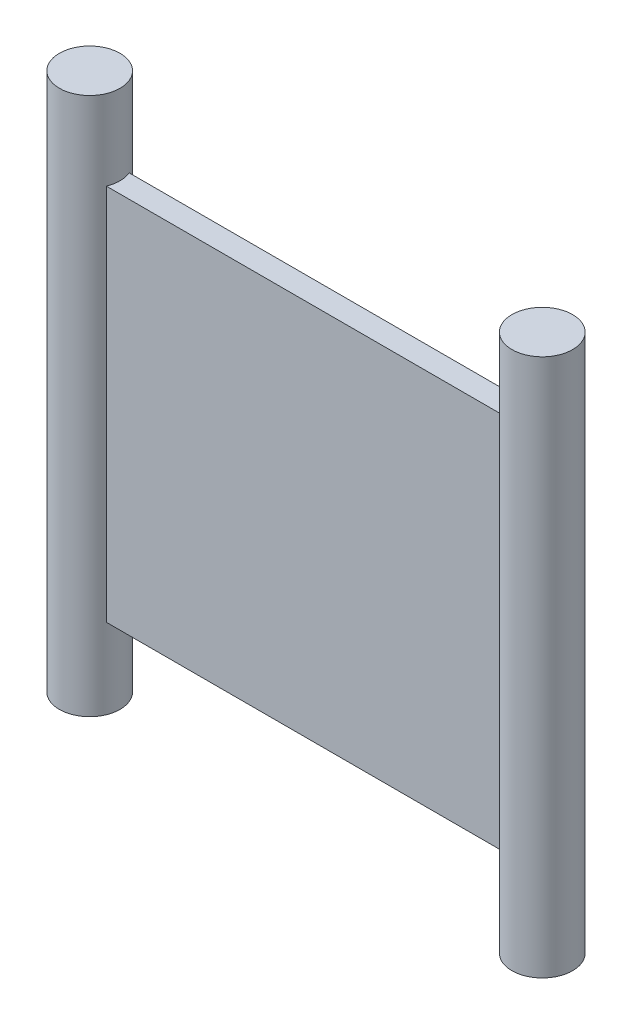
SolidWorks part; units mm, degrees
ref_plane "Front Plane" through (0, 0, 0) normal (0, 0, 1) x (1, 0, 0)
ref_plane "Top Plane" through (0, 0, 0) normal (0, 1, 0) x (1, 0, 0)
ref_plane "Right Plane" through (0, 0, 0) normal (1, 0, 0) x (0, 0, -1)
sketch "Sketch1" plane through (0, 0, 0) normal (0, 1, 0) x (1, 0, 0)
  line L1 (9.885, 0.5) -> (-9.885, 0.5)
  line L2 (9.885, 0.5) -> (9.885, -0.5)
  line L3 (9.885, -0.5) -> (-9.885, -0.5)
  line L4 (-9.885, 0.5) -> (-9.885, -0.5)
  line L5 (9.885, 0.5) -> (-9.885, -0.5) construction
  line L6 (9.885, -0.5) -> (-9.885, 0.5) construction
  point P0 (0, 0)
  dimension "D1" = 19.77
  dimension "D3" = 1
extrude "Boss-Extrude1" add sketch "Sketch1" along normal blind 16.5
ref_plane "Plane1" through (0, 8.25, 0) normal (0, 1, 0) x (1, 0, 0)
sketch "Sketch2" plane through (0, 8.25, 0) normal (0, 1, 0) x (1, 0, 0)
  line L0 (9.885, -0.5) -> (9.885, 0.5) construction
  line L1 (-9.885, 0.5) -> (-9.885, -0.5) construction
  line L2 (9.885, -0.5) -> (9.885, 0.5) construction
  line L3 (-9.885, 0.5) -> (-9.885, -0.5) construction
  circle A0 centre (-9.885, 0) radius 1.325
  circle A1 centre (9.885, 0) radius 1.325
  dimension "D1" = 2.65
extrude "Boss-Extrude2" add sketch "Sketch2" along normal mid plane 23.5
